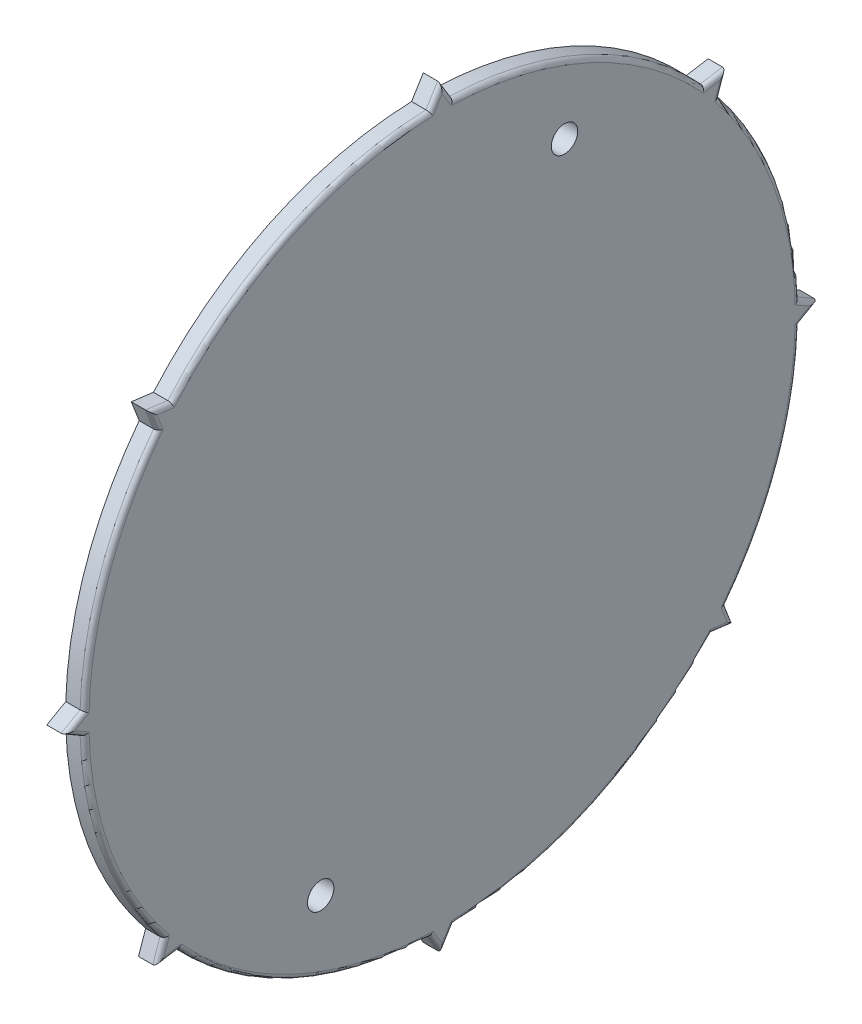
SolidWorks part; units mm, degrees
ref_plane "Plano frontal" through (0, 0, 0) normal (0, 0, 1) x (1, 0, 0)
ref_plane "Plano superior" through (0, 0, 0) normal (0, 1, 0) x (1, 0, 0)
ref_plane "Plano direito" through (0, 0, 0) normal (1, 0, 0) x (0, 0, -1)
sketch "Esboço1" plane through (0, 0, 0) normal (1, 0, 0) x (0, 0, -1)
  line L2 (-0.3099, -9.4949) -> (0, -10)
  line L4 (0, 10) -> (-0.3121, 9.4949)
  line L5 (0, 10) -> (0.3099, 9.4949)
  line L6 (7.5643, 6.5407) -> (6.9795, 6.4449)
  line L7 (7.5643, 6.5407) -> (7.3747, 5.9886)
  line L8 (10, 0) -> (9.4955, 0.2919)
  line L9 (10, 0) -> (9.4957, -0.2865)
  line L10 (0.3121, -9.4949) -> (0, -10)
  line L12 (-10, 0) -> (-9.4955, -0.2919)
  line L13 (-10, 0) -> (-9.4957, 0.2865)
  line L14 (-7.7558, 6.3125) -> (-7.5455, 5.7719)
  line L18 (7.7558, -6.3125) -> (7.1645, -6.2385)
  line L19 (7.7558, -6.3125) -> (7.5465, -5.7706)
  line L20 (-6.9769, -6.4477) -> (-7.5643, -6.5407)
  line L21 (-7.3736, -5.9899) -> (-7.5643, -6.5407)
  line L24 (-7.1671, 6.2356) -> (-7.7558, 6.3125)
  line L25 (-7.5455, 5.7719) -> (-7.7558, 6.3125)
  arc A0 (-0.3121, 9.4949) -> (-7.1671, 6.2356) centre (0, 0) ccw
  arc A2 (6.9795, 6.4449) -> (0.3099, 9.4949) centre (0, 0) ccw
  arc A3 (-7.5455, 5.7719) -> (-9.4957, 0.2865) centre (0, 0) ccw
  arc A4 (-9.4955, -0.2919) -> (-7.3736, -5.9899) centre (0, 0) ccw
  arc A5 (-6.9769, -6.4477) -> (-0.3099, -9.4949) centre (0, 0) ccw
  arc A6 (0.3121, -9.4949) -> (7.1645, -6.2385) centre (0, 0) ccw
  arc A7 (9.4955, 0.2919) -> (7.3747, 5.9886) centre (0, 0) ccw
  arc A8 (7.5465, -5.7706) -> (9.4957, -0.2865) centre (0, 0) ccw
  dimension "D2" = 19
extrude "Ressalto-extrusão1" add sketch "Esboço1" along normal blind 0.5 contours L19 A8 L9 L8 A7 L7 L6 A2 L5 L4 A0 L24 L14 A3 L13 L12 A4 L21 L20 A5 L2 L10 A6 L18
fillet "Filete2" radius 0.12 24 edges at (0.5, -6.2755, -7.4602) (0.5, -8.5805, -4.0775) (0.5, -9.7474, -0.156) (0.5, -9.7475, 0.155) (0.5, -8.6403, 3.9492) (0.5, -6.4942, 7.2706) (0.5, -6.2653, 7.469) (0.5, -3.3153, 8.9027) (0.5, -0.146, 9.7478) (0.5, 0.1433, 9.7478) (0.5, 3.1823, 8.9512) (0.5, 6.0422, 7.6507) (0.5, 6.2741, 7.4614) (0.5, 8.5796, 4.0792) (0.5, 9.7474, 0.156) (0.5, 9.7475, -0.155) (0.5, 8.6395, -3.9509) (0.5, 6.4928, -7.2719) (0.5, 6.2647, -7.4695) (0.5, 3.3145, -8.903) (0.5, 0.146, -9.7478) (0.5, -0.1433, -9.7478) (0.5, -3.1815, -8.9514) (0.5, -6.0415, -7.6512)
sketch "Esboço3" plane through (0.5, 0, 0) normal (1, 0, 0) x (0, 0, -1)
  circle A2 centre (3.2497, 7.1058) radius 0.35
  circle A3 centre (-3.2253, -7.057) radius 0.35
  dimension "D1" = 0.7
  dimension "D2" = 0.7
extrude "Corte-extrusão1" cut sketch "Esboço3" against normal blind 0.5
